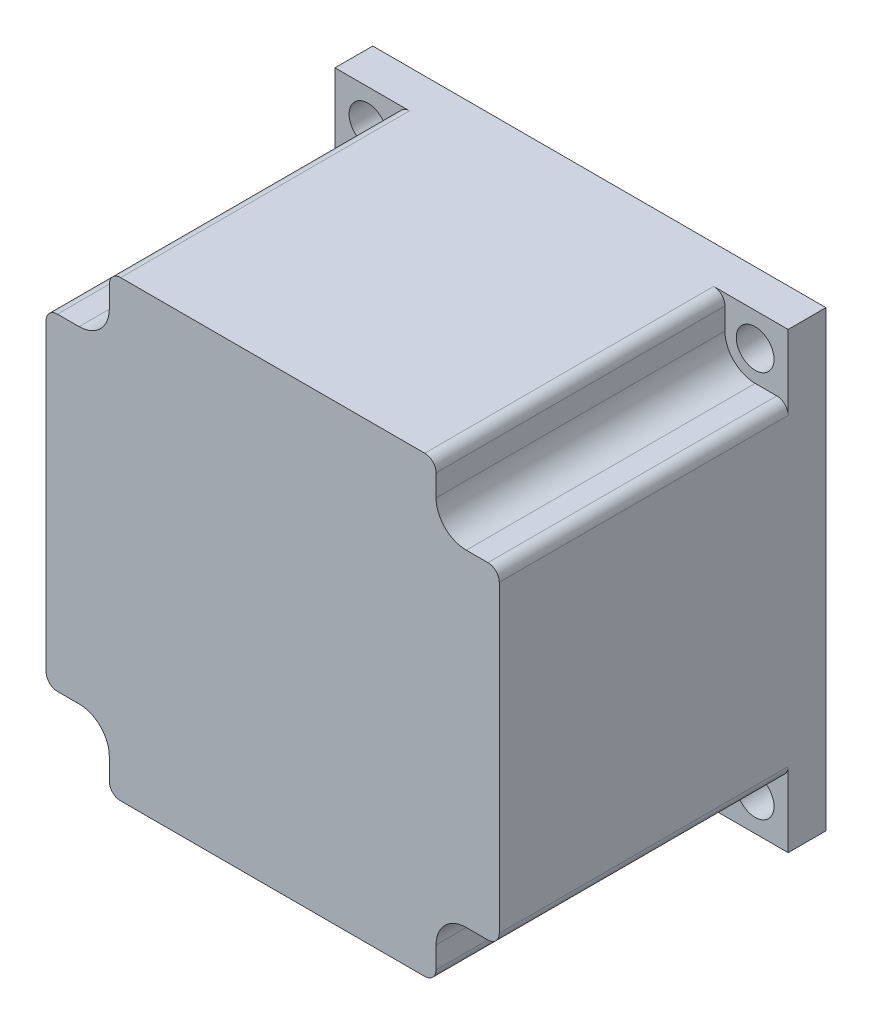
SolidWorks part; units mm, degrees
ref_plane "前视基准面" through (0, 0, 0) normal (0, 0, 1) x (1, 0, 0)
ref_plane "上视基准面" through (0, 0, 0) normal (0, 1, 0) x (1, 0, 0)
ref_plane "右视基准面" through (0, 0, 0) normal (1, 0, 0) x (0, 0, -1)
sketch "草图1" plane through (0, 0, 0) normal (0, 0, 1) x (1, 0, 0)
  line L1 (0, 0) -> (120, 0)
  line L2 (0, 0) -> (0, -120)
  line L3 (0, -120) -> (120, -120)
  line L4 (120, 0) -> (120, -120)
  dimension "D1" = 120
  dimension "D2" = 120
extrude "拉伸1" add sketch "草图1" along normal blind 86.5
sketch "草图2" plane through (0, 0, 0) normal (0, 0, -1) x (-1, 0, 0)
  circle A0 centre (-60, -60) radius 55
extrude "拉伸2" add sketch "草图2" along normal blind 5
sketch "草图3" plane through (0, 0, -5) normal (0, 0, -1) x (-1, 0, 0)
  circle A0 centre (-60, -60) radius 38.5
extrude "拉伸3" add sketch "草图3" along normal blind 5.5
sketch "草图4" plane through (0, 0, -10.5) normal (0, 0, -1) x (-1, 0, 0)
  circle A0 centre (-60, -60) radius 9.5
  dimension "D1" = 19
extrude "拉伸4" add sketch "草图4" along normal blind 29.5
sketch "草图5" plane through (0, 0, 0) normal (0, 0, -1) x (-1, 0, 0)
  circle A0 centre (-8.7348, -111.2652) radius 5
  circle A1 centre (-8.7348, -8.7348) radius 5
  circle A2 centre (-111.2652, -111.2652) radius 5
  circle A3 centre (-111.2652, -8.7348) radius 5
extrude "切除-拉伸1" cut sketch "草图5" against normal through all
sketch "草图6" plane through (0, 0, 86.5) normal (0, 0, 1) x (1, 0, 0)
  line L0 (8.7348, -16.7348) -> (0, -16.7348)
  line L1 (16.7348, -8.7348) -> (16.7348, 0)
  line L2 (0, 0) -> (0, -16.7348)
  line L4 (0, 0) -> (16.7348, 0)
  line L6 (111.2652, -103.2652) -> (120, -103.2652)
  line L12 (120, 0) -> (103.2652, 0)
  line L13 (120, 0) -> (120, -16.7348)
  line L14 (103.2652, -8.7348) -> (103.2652, 0)
  line L15 (111.2652, -16.7348) -> (120, -16.7348)
  line L16 (103.2652, -111.2652) -> (103.2652, -120)
  line L17 (120, -120) -> (120, -103.2652)
  line L18 (120, -120) -> (103.2652, -120)
  line L19 (0, -120) -> (16.7348, -120)
  line L20 (0, -120) -> (0, -103.2652)
  line L21 (16.7348, -111.2652) -> (16.7348, -120)
  line L22 (8.7348, -103.2652) -> (0, -103.2652)
  arc A0 (8.7348, -16.7348) -> (16.7348, -8.7348) centre (8.7348, -8.7348) ccw
  arc A1 (111.2652, -16.7348) -> (103.2652, -8.7348) centre (111.2652, -8.7348) cw
  arc A2 (111.2652, -103.2652) -> (103.2652, -111.2652) centre (111.2652, -111.2652) ccw
  arc A3 (8.7348, -103.2652) -> (16.7348, -111.2652) centre (8.7348, -111.2652) cw
extrude "切除-拉伸2" cut sketch "草图6" against normal blind 76.5
fillet "圆角1" radius 3 8 edges at (103.2652, 0, 48.25) (120, -16.7348, 48.25) (120, -103.2652, 48.25) (103.2652, -120, 48.25) (16.7348, -120, 48.25) (0, -103.2652, 48.25) (16.7348, 0, 48.25) (0, -16.7348, 48.25)
